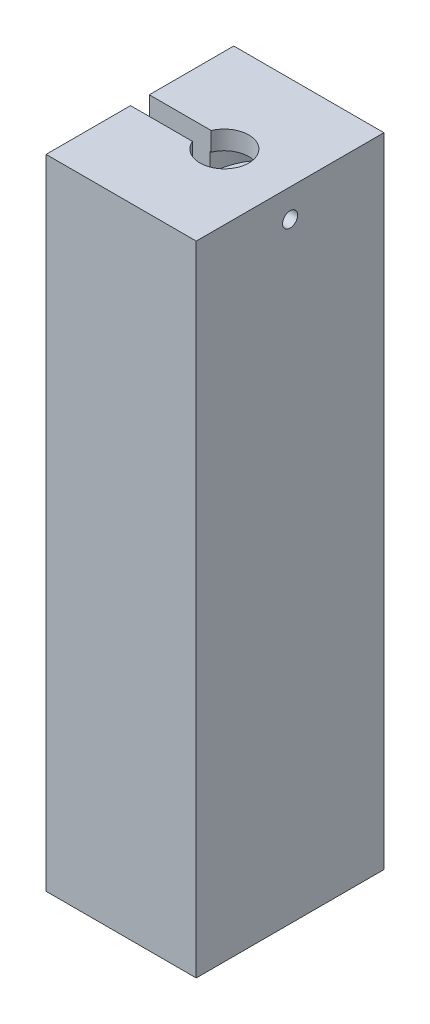
SolidWorks part; units mm, degrees
ref_plane "Front Plane" through (0, 0, 0) normal (0, 0, 1) x (1, 0, 0)
ref_plane "Top Plane" through (0, 0, 0) normal (0, 1, 0) x (1, 0, 0)
ref_plane "Right Plane" through (0, 0, 0) normal (1, 0, 0) x (0, 0, -1)
sketch "Sketch5" plane through (0, 0, 0) normal (0, 1, 0) x (1, 0, 0)
  line L0 (0, 2.5) -> (0, -2.5) construction
  line L1 (-2.25, -2.5) -> (1.75, -2.5)
  line L2 (-2.25, -2.5) -> (-2.25, 2.5)
  line L3 (-2.25, 2.5) -> (1.75, 2.5)
  line L4 (1.75, -2.5) -> (1.75, 2.5)
  dimension "D1" = 4
  dimension "D2" = 5
  dimension "D3" = 1.75
extrude "Boss-Extrude3" add sketch "Sketch5" along normal blind 15
sketch "Sketch3" plane through (0, 0, 0) normal (0, 1, 0) x (1, 0, 0)
  line L0 (-5, 0.75) -> (0, 1.05) construction
  line L3 (0, -1.05) -> (-5, -0.75) construction
  line L4 (-2.5, 0.9) -> (-2, 0.93)
  line L6 (-4.25, 0) -> (-5.75, 0) construction
  line L7 (-2, 0.93) -> (-2, 0.56)
  line L8 (-2.5, 0.9) -> (-5, 0.9)
  line L9 (-2.5, 0.9) -> (-2.5, -0.9) construction
  line L10 (-2.5, -0.9) -> (-5, -0.9)
  line L11 (-5, 0.9) -> (-5, -0.9) construction
  line L12 (-2, 0.96) -> (-1.5, 0.96) construction
  line L13 (-2, 0.96) -> (-2, 0.56) construction
  line L14 (-2, 0.56) -> (-1.5, 0.56)
  line L15 (-1.5, 0.96) -> (-1.5, 0.56)
  line L16 (-1.5, -0.56) -> (-2, -0.56)
  line L17 (-1.5, -0.56) -> (-1.5, -0.96)
  line L18 (-1.5, -0.96) -> (-2, -0.96) construction
  line L19 (-2, -0.56) -> (-2, -0.96) construction
  line L21 (-2.5, -0.9) -> (-2, -0.93)
  line L22 (-2, -0.93) -> (-2, -0.56)
  line L23 (-1.5, 0.96) -> (0, 1.05)
  line L24 (0, -1.05) -> (-1.5, -0.96)
  circle A2 centre (0, 0) radius 0.6 construction
  circle A3 centre (0, 0) radius 0.4 construction
  circle A4 centre (-5, 0) radius 0.35 construction
  circle A5 centre (0, 0) radius 1.05 construction
  circle A6 centre (-5, 0) radius 0.75 construction
  arc A7 (-5, 0.9) -> (-5, -0.9) centre (-5, 0) ccw
  arc A8 (0, 1.05) -> (0, -1.05) centre (0, 0) cw
  point P4 (-2, -0.93)
  point P15 (-5, 0)
  point P16 (-2, 0.93)
  point P22 (-5, 0)
  dimension "D2" = 1.2
  dimension "D3" = 0.8
  dimension "D4" = 0.7
  dimension "D6" = 5
  dimension "D1" = 1.5
  dimension "D5" = 2.1
  dimension "D7" = 0.4
  dimension "D9" = 2.5
  dimension "D10" = 1.8
  dimension "D11" = 2.5
  dimension "D12" = 0.5
  dimension "D14" = 1.5
extrude "Cut-Extrude1" cut sketch "Sketch3" along normal through all
fillet "Fillet1" radius 0.125 4 edges at (-2, 7.5, -0.56) (-1.5, 7.5, 0.56) (-1.5, 7.5, -0.56) (-2, 7.5, 0.56)
sketch "Sketch6" plane through (0, 15, 0) normal (0, 1, 0) x (1, 0, 0)
  line L1 (-2.25, 2.5) -> (1.75, 2.5)
  line L2 (-2.25, 2.5) -> (-2.25, -2.5)
  line L3 (-2.25, -2.5) -> (1.75, -2.5)
  line L4 (1.75, 2.5) -> (1.75, -2.5)
  circle A0 centre (0, 0) radius 0.425
  dimension "D1" = 0.85
extrude "Boss-Extrude4" add sketch "Sketch6" along normal blind 1
sketch "Sketch7" plane through (0, 16, 0) normal (0, 1, 0) x (1, 0, 0)
  line L0 (-2.25, -2.5) -> (1.75, -2.5) construction
  line L1 (-2.25, 2.5) -> (1.75, 2.5)
  line L2 (-2.25, 2.5) -> (-2.25, -2.5)
  line L3 (-2.25, -2.5) -> (1.75, -2.5)
  line L4 (1.75, 2.5) -> (1.75, -2.5)
  line L5 (1.75, -2.5) -> (1.75, 2.5) construction
  circle A0 centre (0, 0) radius 0.65 construction
  ellipse E0 centre (0, 0) end of major axis (0, 1.3) minor radius 0.65
  dimension "D1" = 1.3
  dimension "D2" = 2.6
extrude "Boss-Extrude5" add sketch "Sketch7" along normal blind 0.5
sketch "Sketch9" plane through (0, 16.5, 0) normal (0, 1, 0) x (1, 0, 0)
  line L1 (-2.25, 2.5) -> (1.75, 2.5)
  line L2 (-2.25, 2.5) -> (-2.25, -2.5)
  line L3 (-2.25, -2.5) -> (1.75, -2.5)
  line L4 (1.75, 2.5) -> (1.75, -2.5)
  circle A0 centre (0, 0) radius 0.65
  circle A2 centre (0, 0) radius 0.65 construction
extrude "Boss-Extrude6" add sketch "Sketch9" along normal blind 0.5
sketch "Sketch10" plane through (0, 17, 0) normal (0, 1, 0) x (1, 0, 0)
  line L0 (-2.25, 2.5) -> (-2.25, -2.5) construction
  line L1 (-2.25, -0.25) -> (-0.6, -0.25)
  line L2 (-2.25, -0.25) -> (-2.25, 0.25)
  line L3 (-2.25, 0.25) -> (-0.6, 0.25)
  line L4 (-0.6, -0.25) -> (-0.6, 0.25)
  line L5 (-2.25, 2.5) -> (-2.25, -2.5) construction
  circle A0 centre (0, 0) radius 0.65 construction
  point P6 (-2.25, 0)
  point P7 (0, 0)
  point P8 (0, 0)
  point P11 (0, 0)
  dimension "D1" = 0.5
extrude "Cut-Extrude2" cut sketch "Sketch10" against normal up to surface (1 mm away) up to face at (0, 16, 0.425)
sketch "Sketch11" plane through (1.75, 0, 0) normal (1, 0, 0) x (0, 0, -1)
  line L0 (0, 16) -> (0, 16.5) construction
  line L1 (1.3, 16) -> (-1.3, 16) construction
  circle A0 centre (0, 16.25) radius 0.2
  point P2 (0, 0)
  point P8 (0, 0)
  dimension "D1" = 0.4
extrude "Cut-Extrude3" cut sketch "Sketch11" against normal up to next
